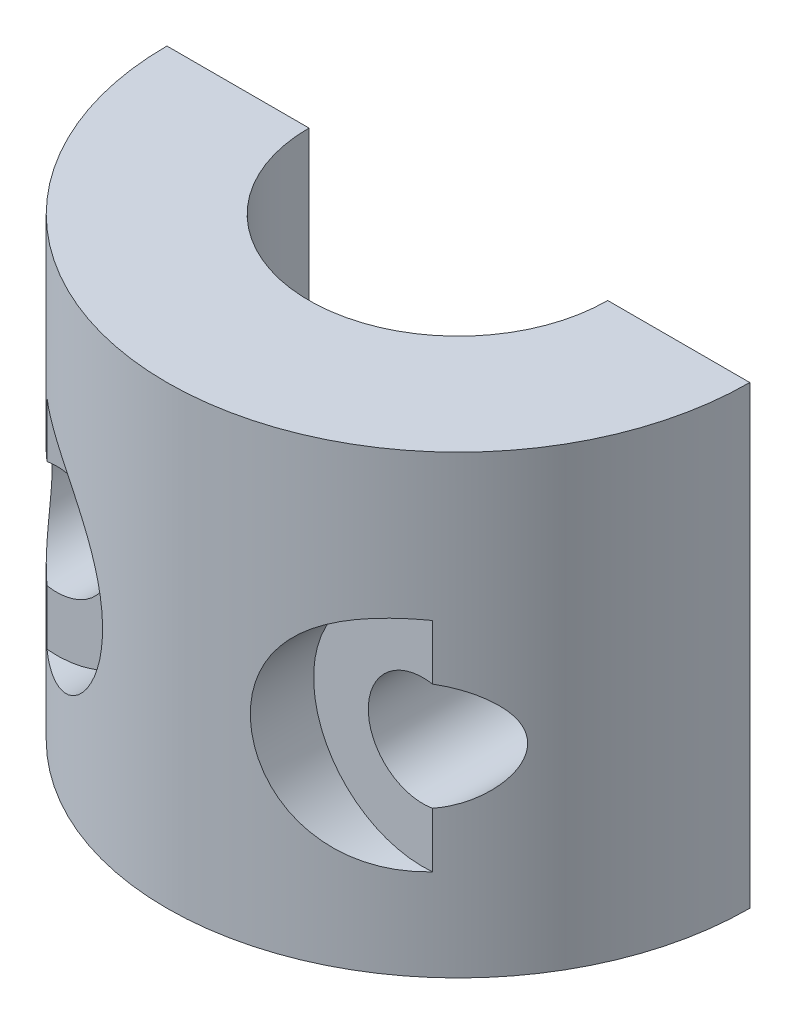
SolidWorks part; units mm, degrees
ref_plane "Спереди" through (0, 0, 0) normal (0, 0, 1) x (1, 0, 0)
ref_plane "Сверху" through (0, 0, 0) normal (0, 1, 0) x (1, 0, 0)
ref_plane "Справа" through (0, 0, 0) normal (1, 0, 0) x (0, 0, -1)
sketch "Sketch1" plane through (0, 0, 0) normal (0, 0, 1) x (1, 0, 0)
  line L0 (-0.75, 0) -> (0.75, 0)
  line L1 (-4, 3.5) -> (4, 3.5)
  line L2 (-4, 3.5) -> (-4, -3.5)
  line L3 (-4, -3.5) -> (4, -3.5)
  line L4 (4, 3.5) -> (4, -3.5)
  line L5 (-4, 3.5) -> (4, -3.5) construction
  line L6 (-4, -3.5) -> (4, 3.5) construction
  line L7 (-0.75, 0) -> (-0.75, -3.5)
  line L8 (0.75, 0) -> (0.75, -3.5)
  line L9 (-2, 3.5) -> (2, 3.5)
  line L10 (-2, 3.5) -> (-2, -2)
  line L11 (2, 3.5) -> (2, -2)
  line L12 (-2, -2) -> (-0.75, -2)
  line L13 (0.75, -2) -> (2, -2)
  line L14 (0, 0) -> (0, -3.5) construction
  point P0 (0, 0)
  point P9 (0, 0)
  point P14 (0, 3.5)
  dimension "D1" = 7
  dimension "D2" = 1.5
  dimension "D3" = 4
  dimension "D4" = 5.5
  dimension "D5" = 8
revolve "Revolve2" add sketch "Sketch1" angle 360 about L14
sketch "Sketch8" plane through (0, -2, 0) normal (0, 1, 0) x (1, 0, 0)
  circle A0 centre (0, 0) radius 2
  circle A1 centre (0, 0) radius 2 construction
extrude "Boss-Extrude2" add sketch "Sketch8" along normal blind 5.5
sketch "Sketch9" plane through (0, -2, 0) normal (0, -1, 0) x (1, 0, 0)
  circle A0 centre (0, 0) radius 2.05
  dimension "D1" = 4.1
extrude "Cut-Extrude3" cut sketch "Sketch9" against normal blind 5.5
sketch "Sketch10" plane through (0, 0, 0) normal (0, 0, 1) x (1, 0, 0)
  line L0 (0, 0) -> (0, -3.5) construction
  line L1 (-4, -3.5) -> (4, -3.5) construction
  line L3 (-2.5136, 0) -> (2.5136, 0)
  circle A0 centre (2.5136, 0) radius 0.75
  circle A1 centre (-2.5136, 0) radius 0.75
  point P7 (-2.7115, -2.2462)
  point P8 (2.5136, 0)
  point P9 (2.7115, -2.516)
  point P19 (0, 0)
  dimension "D2" = 1.5
extrude "Cut-Extrude4" cut sketch "Sketch10" against normal blind 3 and the other way blind 5.5
sketch "Sketch12" plane through (0, -2, 0) normal (0, 1, 0) x (1, 0, 0)
  circle A0 centre (0, 0) radius 2.0321
extrude "Cut-Extrude5" cut sketch "Sketch12" along normal blind 1.2
sketch "Sketch15" plane through (0, 0, 0) normal (0, 0, 1) x (1, 0, 0)
  circle A0 centre (2.5136, 0) radius 1.5
  circle A1 centre (-2.5136, 0) radius 1.5
  dimension "D1" = 3
extrude "Cut-Extrude11" cut sketch "Sketch15" against normal blind 21.2 from offset 3 offset against normal yes
sketch "Sketch16" plane through (0, 0, 0) normal (0, 0, 1) x (1, 0, 0)
  circle A0 centre (2.5136, 0) radius 1.5
  circle A1 centre (-2.5136, 0) radius 1.5
  dimension "D1" = 3
extrude "Cut-Extrude12" cut sketch "Sketch16" along normal blind 21.2 from offset 3
sketch "Sketch17" plane through (0, 0, 0) normal (0, 0, 1) x (1, 0, 0)
  line L1 (-6.4823, 5.3838) -> (5.6122, 5.3838)
  line L2 (-6.4823, 5.3838) -> (-6.4823, -7.211)
  line L3 (-6.4823, -7.211) -> (5.6122, -7.211)
  line L4 (5.6122, 5.3838) -> (5.6122, -7.211)
extrude "Cut-Extrude14" cut sketch "Sketch17" against normal blind 21.2 contours L3 L4 L1 L2
sketch "Sketch18" plane through (0, -3.5, 0) normal (0, -1, 0) x (1, 0, 0)
  circle A0 centre (0, 0) radius 5.5962
extrude "Cut-Extrude15" cut sketch "Sketch18" against normal blind 0.75
